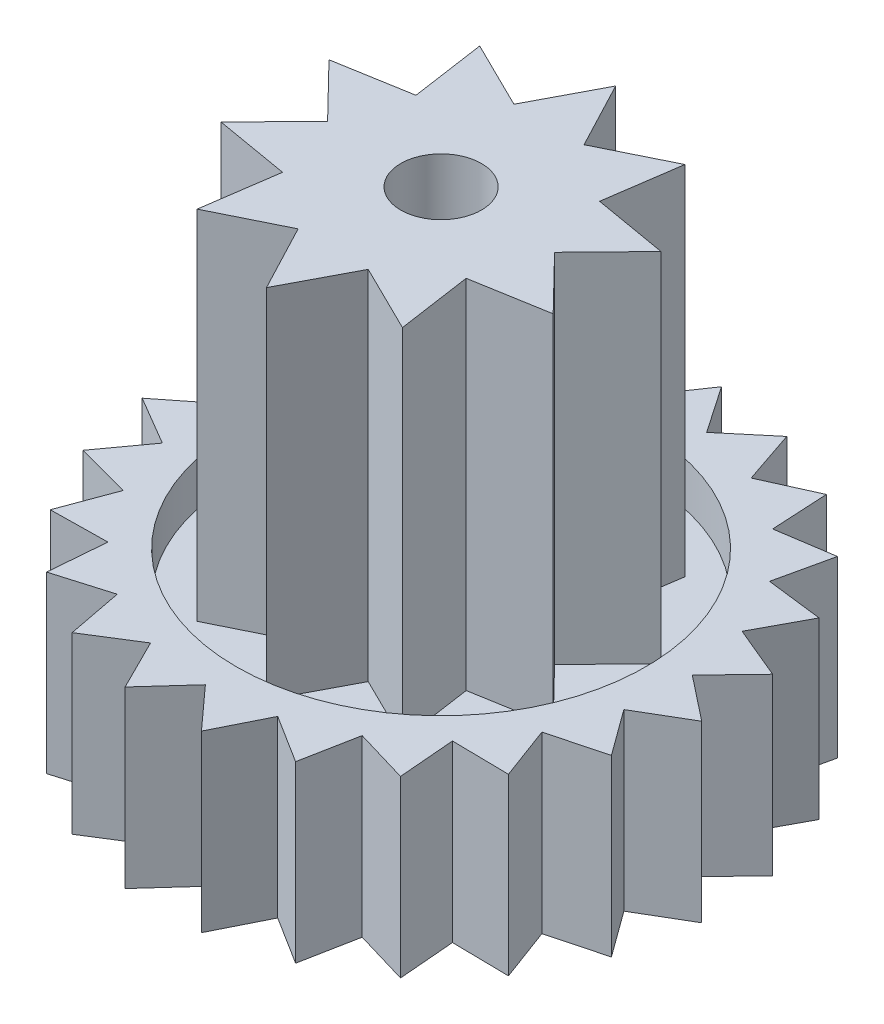
SolidWorks part; units mm, degrees
ref_plane "Front Plane" through (0, 0, 0) normal (0, 0, 1) x (1, 0, 0)
ref_plane "Top Plane" through (0, 0, 0) normal (0, 1, 0) x (1, 0, 0)
ref_plane "Right Plane" through (0, 0, 0) normal (1, 0, 0) x (0, 0, -1)
sketch "Sketch1" plane through (0, 0, 0) normal (0, 0, 1) x (1, 0, 0)
  line L0 (0, 11.18) -> (0, 0)
  line L1 (0, -55) -> (0, 55) construction
  line L2 (0, 0) -> (1.73, 0)
  line L3 (55, 0) -> (-55, 0) construction
  line L4 (6.425, 0) -> (6.425, 4)
  line L5 (6.425, 4) -> (4.69, 4)
  line L6 (4, 3) -> (4, 11.18)
  line L7 (4, 11.18) -> (0, 11.18)
  line L8 (4.69, 4) -> (4.69, 3)
  line L9 (4.69, 3) -> (4, 3)
  line L10 (4.69, 0) -> (6.425, 0)
  line L11 (1.73, 1.44) -> (4.69, 1.44)
  line L12 (1.73, 1.44) -> (1.73, 0)
  line L14 (4.69, 1.44) -> (4.69, 0)
  dimension "D1" = 4
  dimension "D2" = 6.425
  dimension "D3" = 11.18
  dimension "D4" = 4
  dimension "D5" = 1.44
  dimension "D6" = 1.73
  dimension "D7" = 4.69
  dimension "D8" = 1
revolve "Revolve1" add sketch "Sketch1" angle 360 about L0
sketch "Sketch2" plane through (0, 4, 0) normal (0, 1, 0) x (1, 0, 0)
  line L0 (0, 6.425) -> (-0.7353, 5.3497)
  line L1 (0, -6.149) -> (0, 6.149) construction
  line L2 (-0.7353, 5.3497) -> (0, 0) construction
  line L3 (0, 0) -> (0.7353, 5.3497) construction
  line L4 (0.7353, 5.3497) -> (0, 6.425)
  line L5 (1.7334, 6.1867) -> (0.7353, 5.3497)
  line L6 (2.1514, 4.9529) -> (1.7334, 6.1867)
  line L7 (3.3383, 5.4896) -> (2.1514, 4.9529)
  line L8 (3.4079, 4.1888) -> (3.3383, 5.4896)
  line L9 (4.6956, 4.3854) -> (3.4079, 4.1888)
  line L10 (4.4116, 3.1141) -> (4.6956, 4.3854)
  line L11 (5.7047, 2.9559) -> (4.4116, 3.1141)
  line L12 (5.0882, 1.8083) -> (5.7047, 2.9559)
  line L13 (6.2906, 1.3072) -> (5.0882, 1.8083)
  line L14 (5.3874, 0.3685) -> (6.2906, 1.3072)
  line L15 (6.41, -0.4385) -> (5.3874, 0.3685)
  line L16 (5.2871, -1.0987) -> (6.41, -0.4385)
  line L17 (6.054, -2.1516) -> (5.2871, -1.0987)
  line L18 (4.7946, -2.4844) -> (6.054, -2.1516)
  line L19 (5.249, -3.7052) -> (4.7946, -2.4844)
  line L20 (3.9465, -3.6858) -> (5.249, -3.7052)
  line L21 (4.0547, -4.9839) -> (3.9465, -3.6858)
  line L22 (2.8058, -4.6139) -> (4.0547, -4.9839)
  line L23 (2.5597, -5.8931) -> (2.8058, -4.6139)
  line L24 (1.4569, -5.1998) -> (2.5597, -5.8931)
  line L25 (0.8749, -6.3652) -> (1.4569, -5.1998)
  line L26 (0, -5.4) -> (0.8749, -6.3652)
  line L27 (-0.8749, -6.3652) -> (0, -5.4)
  line L28 (-1.4569, -5.1998) -> (-0.8749, -6.3652)
  line L29 (-2.5597, -5.8931) -> (-1.4569, -5.1998)
  line L30 (-2.8058, -4.6139) -> (-2.5597, -5.8931)
  line L31 (-4.0547, -4.9839) -> (-2.8058, -4.6139)
  line L32 (-3.9465, -3.6858) -> (-4.0547, -4.9839)
  line L33 (-5.249, -3.7052) -> (-3.9465, -3.6858)
  line L34 (-4.7946, -2.4844) -> (-5.249, -3.7052)
  line L35 (-6.054, -2.1516) -> (-4.7946, -2.4844)
  line L36 (-5.2871, -1.0987) -> (-6.054, -2.1516)
  line L37 (-6.41, -0.4385) -> (-5.2871, -1.0987)
  line L38 (-5.3874, 0.3685) -> (-6.41, -0.4385)
  line L39 (-6.2906, 1.3072) -> (-5.3874, 0.3685)
  line L40 (-5.0882, 1.8083) -> (-6.2906, 1.3072)
  line L41 (-5.7047, 2.9559) -> (-5.0882, 1.8083)
  line L42 (-4.4116, 3.1141) -> (-5.7047, 2.9559)
  line L43 (-4.6956, 4.3854) -> (-4.4116, 3.1141)
  line L44 (-3.4079, 4.1888) -> (-4.6956, 4.3854)
  line L45 (-3.3383, 5.4896) -> (-3.4079, 4.1888)
  line L46 (-2.1514, 4.9529) -> (-3.3383, 5.4896)
  line L47 (-1.7334, 6.1867) -> (-2.1514, 4.9529)
  line L48 (-0.7353, 5.3497) -> (-1.7334, 6.1867)
  circle A0 centre (0, 0) radius 5.4 construction
  circle A1 centre (0, 0) radius 6.425 construction
  circle A4 centre (0, 0) radius 6.925
  circle A5 centre (0, 0) radius 6.925
  point P82 (0, 0)
  dimension "D4" = 10.8
  dimension "D2" = 15.652
  dimension "D1" = 0.5
  dimension "D3" = 23
extrude "Cut-Extrude1" cut sketch "Sketch2" against normal through all
sketch "Sketch3" plane through (0, 11.18, 0) normal (0, 1, 0) x (1, 0, 0)
  line L0 (0, 4) -> (-0.8034, 2.4727)
  line L1 (0, -6.149) -> (0, 6.149) construction
  line L2 (-0.8034, 2.4727) -> (0, 0) construction
  line L3 (0, 0) -> (0.8034, 2.4727) construction
  line L4 (0.8034, 2.4727) -> (0, 4)
  line L5 (2.3511, 3.2361) -> (0.8034, 2.4727)
  line L6 (2.1034, 1.5282) -> (2.3511, 3.2361)
  line L7 (3.8042, 1.2361) -> (2.1034, 1.5282)
  line L8 (2.6, 0) -> (3.8042, 1.2361)
  line L9 (3.8042, -1.2361) -> (2.6, 0)
  line L10 (2.1034, -1.5282) -> (3.8042, -1.2361)
  line L11 (2.3511, -3.2361) -> (2.1034, -1.5282)
  line L12 (0.8034, -2.4727) -> (2.3511, -3.2361)
  line L13 (0, -4) -> (0.8034, -2.4727)
  line L14 (-0.8034, -2.4727) -> (0, -4)
  line L15 (-2.3511, -3.2361) -> (-0.8034, -2.4727)
  line L16 (-2.1034, -1.5282) -> (-2.3511, -3.2361)
  line L17 (-3.8042, -1.2361) -> (-2.1034, -1.5282)
  line L18 (-2.6, 0) -> (-3.8042, -1.2361)
  line L19 (-3.8042, 1.2361) -> (-2.6, 0)
  line L20 (-2.1034, 1.5282) -> (-3.8042, 1.2361)
  line L21 (-2.3511, 3.2361) -> (-2.1034, 1.5282)
  line L22 (-0.8034, 2.4727) -> (-2.3511, 3.2361)
  circle A0 centre (0, 0) radius 2.6 construction
  circle A1 centre (0, 0) radius 4 construction
  circle A4 centre (0, 0) radius 4.5
  circle A5 centre (0, 0) radius 4.5
  point P43 (0, 0)
  dimension "D2" = 5.2
  dimension "D1" = 36
  dimension "D3" = 0.5
  dimension "D4" = 10
extrude "Cut-Extrude2" cut sketch "Sketch3" against normal up to surface (8.18 mm away) up to face at (0, 3, 4)
sketch "Sketch4" plane through (0, 11.18, 0) normal (0, 1, 0) x (1, 0, 0)
  circle A0 centre (0, 0) radius 0.925
  dimension "D1" = 1.85
extrude "Cut-Extrude3" cut sketch "Sketch4" against normal through all
